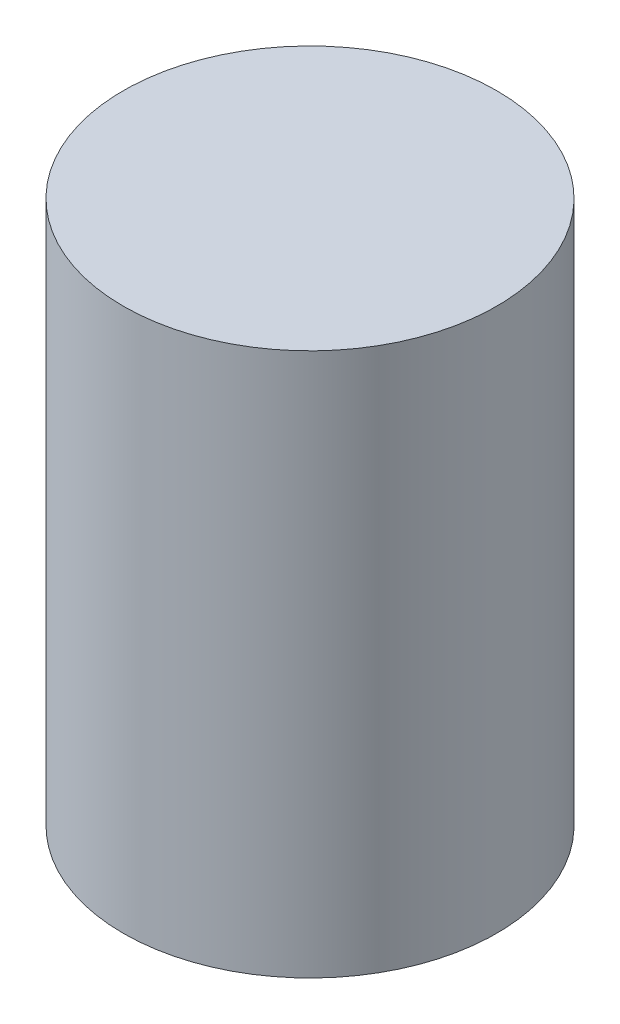
SolidWorks part; units mm, degrees
ref_plane "Front Plane" through (0, 0, 0) normal (0, 0, 1) x (1, 0, 0)
ref_plane "Top Plane" through (0, 0, 0) normal (0, 1, 0) x (1, 0, 0)
ref_plane "Right Plane" through (0, 0, 0) normal (1, 0, 0) x (0, 0, -1)
sketch "Sketch1" plane through (0, 0, 0) normal (0, 1, 0) x (1, 0, 0)
  circle A0 centre (0, 0) radius 2.75
  dimension "D1" = 5.5
extrude "Boss-Extrude1" add sketch "Sketch1" along normal mid plane 8
